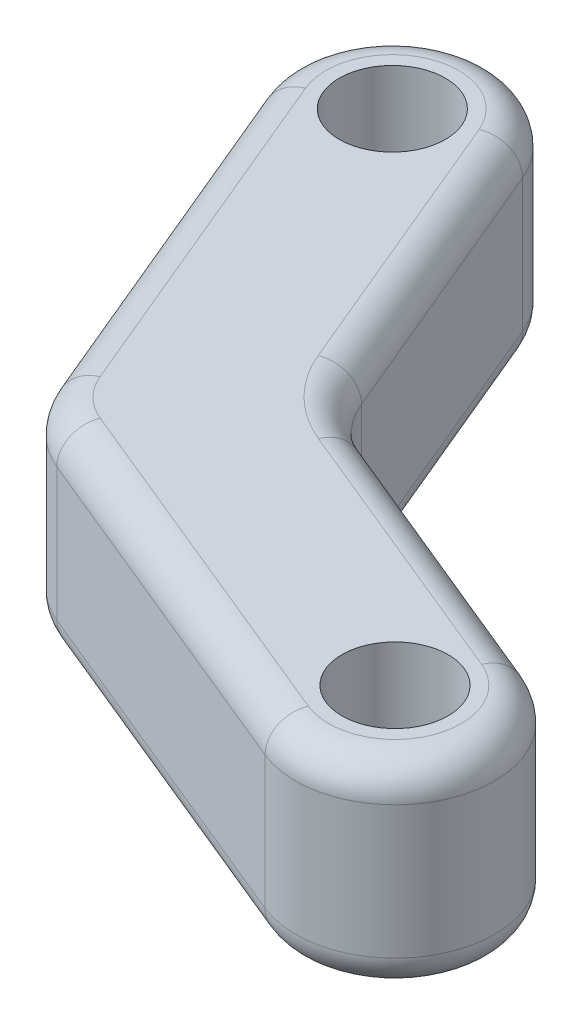
SolidWorks part; units mm, degrees
ref_plane "Front Plane" through (0, 0, 0) normal (0, 0, 1) x (1, 0, 0)
ref_plane "Top Plane" through (0, 0, 0) normal (0, 1, 0) x (1, 0, 0)
ref_plane "Right Plane" through (0, 0, 0) normal (1, 0, 0) x (0, 0, -1)
sketch "Sketch1" plane through (0, 0, 0) normal (0, 1, 0) x (1, 0, 0)
  line L26 (-17.8486, 13.8446) -> (-13.4152, 3.2214)
  line L27 (-11.7873, 1.6021) -> (-1.1407, -2.7747)
  line L28 (-12.3114, 16.1554) -> (-8.8352, 7.8258)
  line L29 (-7.2073, 6.2065) -> (1.1407, 2.7747)
  circle A14 centre (-15.08, 15) radius 1.6
  circle A15 centre (0, 0) radius 1.6
  arc A17 (-1.1407, -2.7747) -> (1.1407, 2.7747) centre (0, 0) ccw
  arc A18 (-17.8486, 13.8446) -> (-12.3114, 16.1554) centre (-15.08, 15) cw
  arc A19 (-8.8352, 7.8258) -> (-7.2073, 6.2065) centre (-6.0666, 8.9812) ccw
  arc A20 (-13.4152, 3.2214) -> (-11.7873, 1.6021) centre (-10.6466, 4.3768) ccw
  point P3 (-11.5181, 3.5007)
  dimension "D1" = 3
extrude "Boss-Extrude1" add sketch "Sketch1" along normal blind 6
fillet "Fillet2" radius 1 16 edges at (-8.1823, 0, -6.8543) (-8.1823, 6, -6.8543) (-3.0333, 0, -4.4906) (2.7747, 0, 1.1407) (-6.464, 0, 0.5863) (-12.7623, 0, -2.2499) (-15.6319, 0, -8.533) (-16.2354, 0, -17.7686) (-10.5733, 0, -11.9906) (-3.0333, 6, -4.4906) (2.7747, 6, 1.1407) (-6.464, 6, 0.5863) (-12.7623, 6, -2.2499) (-15.6319, 6, -8.533) (-16.2354, 6, -17.7686) (-10.5733, 6, -11.9906)
